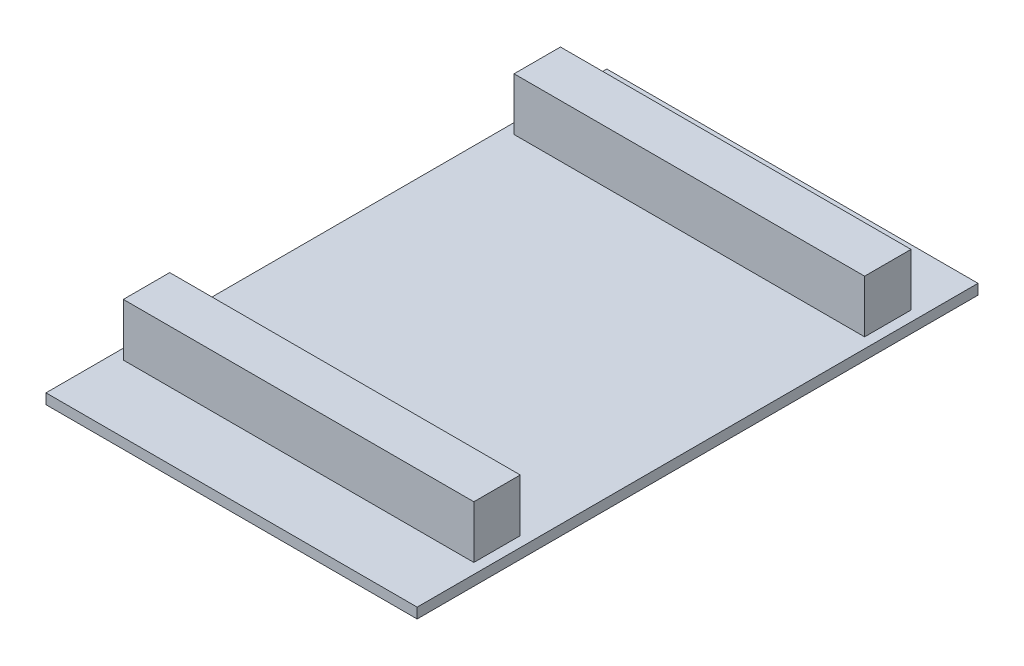
SolidWorks part; units mm, degrees
ref_plane "Plano frontal" through (0, 0, 0) normal (0, 0, 1) x (1, 0, 0)
ref_plane "Plano superior" through (0, 0, 0) normal (0, 1, 0) x (1, 0, 0)
ref_plane "Plano direito" through (0, 0, 0) normal (1, 0, 0) x (0, 0, -1)
sketch "Esboço1" plane through (0, 0, 0) normal (0, 1, 0) x (1, 0, 0)
  line L1 (-18, 27.2) -> (18, 27.2)
  line L2 (-18, 27.2) -> (-18, -27.2)
  line L3 (-18, -27.2) -> (18, -27.2)
  line L4 (18, 27.2) -> (18, -27.2)
  line L5 (-18, 27.2) -> (18, -27.2) construction
  line L6 (-18, -27.2) -> (18, 27.2) construction
  point P0 (0, 0)
  dimension "D1" = 36
  dimension "D2" = 54.4
extrude "Ressalto-extrusão1" add sketch "Esboço1" along normal blind 1
sketch "Esboço2" plane through (0, 1, 0) normal (0, 1, 0) x (1, 0, 0)
  line L1 (-17, -16.2) -> (17, -16.2)
  line L3 (-17, -20.7) -> (17, -20.7)
  line L5 (17, 21.7) -> (-17, 21.7)
  line L6 (-17, -16.2) -> (-17, -20.7)
  line L7 (17, -16.2) -> (17, -20.7)
  line L8 (17, 21.7) -> (17, 17.2)
  line L9 (17, 17.2) -> (-17, 17.2)
  line L10 (-17, 21.7) -> (-17, 17.2)
  dimension "D1" = 4.5
  dimension "D2" = 6.5
  dimension "D3" = 17
  dimension "D4" = 4.5
  dimension "D5" = 5.5
  dimension "D6" = 17
extrude "Ressalto-extrusão2" add sketch "Esboço2" along normal blind 5.1
